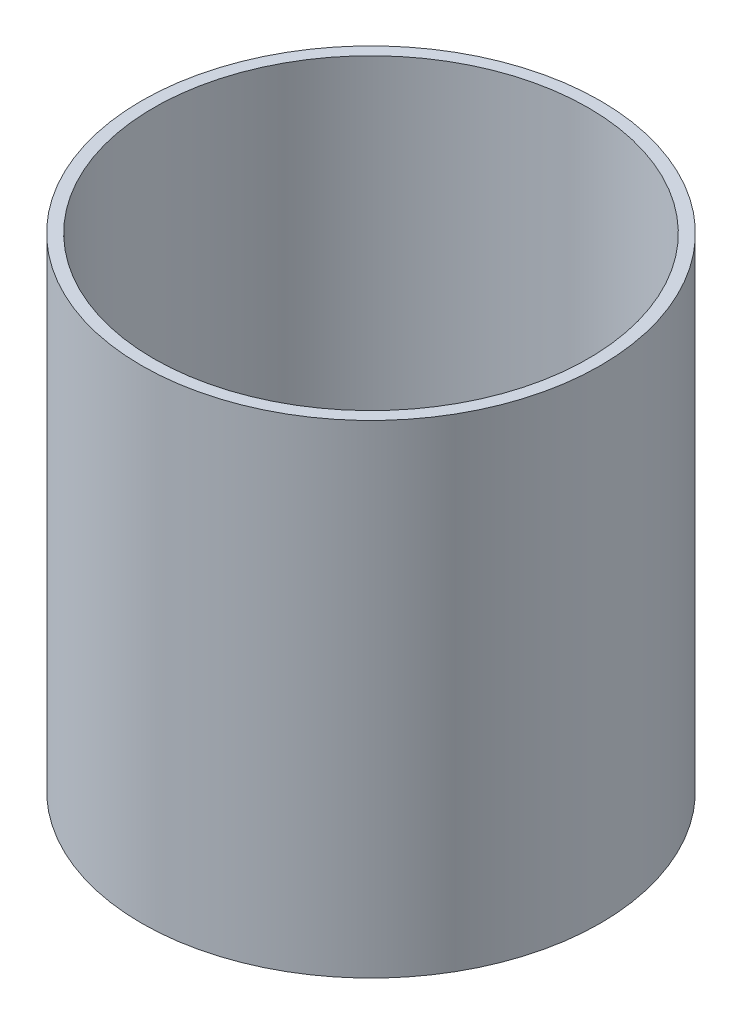
SolidWorks part; units mm, degrees
ref_plane "Front Plane" through (0, 0, 0) normal (0, 0, 1) x (1, 0, 0)
ref_plane "Top Plane" through (0, 0, 0) normal (0, 1, 0) x (1, 0, 0)
ref_plane "Right Plane" through (0, 0, 0) normal (1, 0, 0) x (0, 0, -1)
sketch "Sketch2" plane through (0, 0, 0) normal (0, 1, 0) x (1, 0, 0)
  circle A0 centre (0, 0) radius 36
  circle A1 centre (0, 0) radius 38
  dimension "D1" = 2
  dimension "D2" = 76
extrude "Boss-Extrude1" add sketch "Sketch2" along normal blind 80
